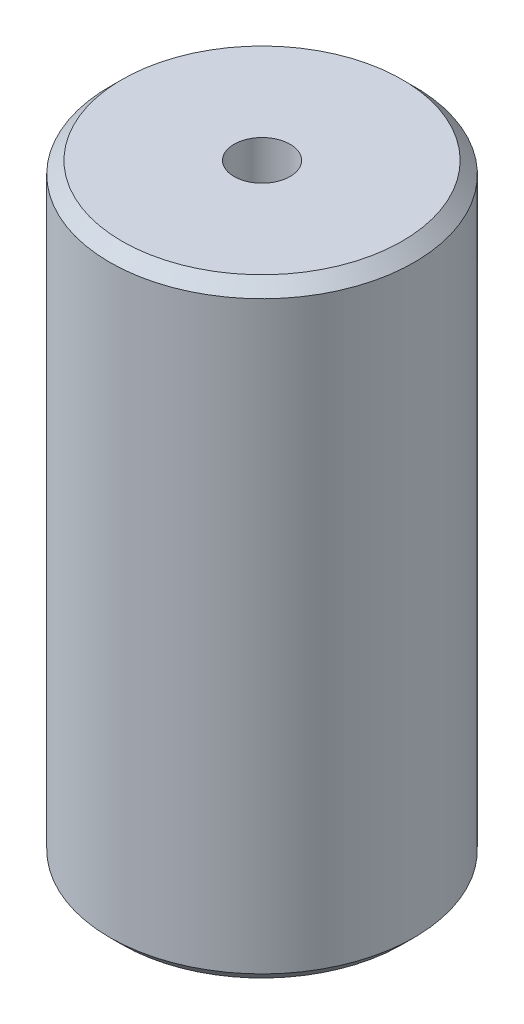
SolidWorks part; units mm, degrees
ref_plane "Front Plane" through (0, 0, 0) normal (0, 0, 1) x (1, 0, 0)
ref_plane "Top Plane" through (0, 0, 0) normal (0, 1, 0) x (1, 0, 0)
ref_plane "Right Plane" through (0, 0, 0) normal (1, 0, 0) x (0, 0, -1)
sketch "Sketch2" plane through (0, 0, 0) normal (0, 1, 0) x (1, 0, 0)
  circle A0 centre (0, 0) radius 6.25
  dimension "D1" = 12.5
extrude "Boss-Extrude1" add sketch "Sketch2" along normal blind 9
sketch "Sketch3" plane through (0, 9, 0) normal (0, 1, 0) x (1, 0, 0)
  circle A0 centre (0, 0) radius 6.25
  dimension "D1" = 12.5
extrude "Boss-Extrude2" add sketch "Sketch3" along normal blind 7
sketch "Sketch4" plane through (0, 16, 0) normal (0, 1, 0) x (1, 0, 0)
  circle A0 centre (0, 0) radius 6.25
  circle A1 centre (0, 0) radius 6.25 construction
extrude "Boss-Extrude3" add sketch "Sketch4" along normal blind 9
sketch "Sketch5" plane through (0, 0, 0) normal (0, -1, 0) x (1, 0, 0)
  circle A0 centre (0, 0) radius 2
  dimension "D1" = 4
extrude "Cut-Extrude1" cut sketch "Sketch5" against normal blind 12.5
sketch "Sketch6" plane through (0, 25, 0) normal (0, 1, 0) x (1, 0, 0)
  circle A0 centre (0, 0) radius 1.15
  dimension "D1" = 2.3
extrude "Cut-Extrude2" cut sketch "Sketch6" against normal blind 12.5
chamfer "Chamfer2" distance 0.5 angle 45 2 edges at (0, 25, 6.25) (0, 0, 6.25)
